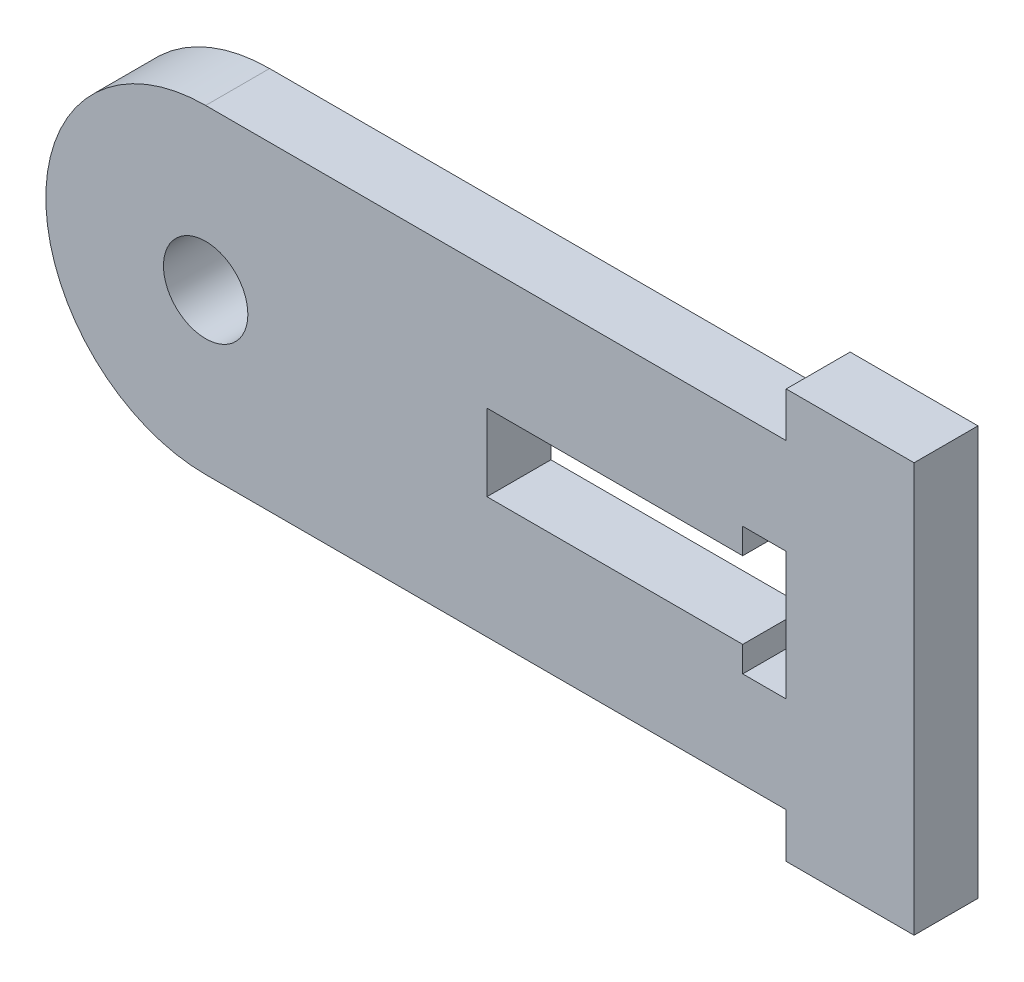
SolidWorks part; units mm, degrees
ref_plane "Front Plane" through (0, 0, 0) normal (0, 0, 1) x (1, 0, 0)
ref_plane "Top Plane" through (0, 0, 0) normal (0, 1, 0) x (1, 0, 0)
ref_plane "Right Plane" through (0, 0, 0) normal (1, 0, 0) x (0, 0, -1)
sketch "Sketch1" plane through (0, 0, 0) normal (0, 0, 1) x (1, 0, 0)
  line L0 (0, -6.25) -> (22.7, -6.25)
  line L1 (-12.7, 12.7) -> (12.7, 12.7)
  line L2 (-12.7, 12.7) -> (-12.7, -12.7)
  line L3 (-12.7, -12.7) -> (12.7, -12.7)
  line L4 (12.7, 12.7) -> (12.7, -12.7)
  line L5 (0, 6.25) -> (22.7, 6.25)
  line L6 (22.7, 6.25) -> (22.7, -6.25)
  circle A0 centre (0, 0) radius 1.65
  arc A1 (0, 6.25) -> (0, -6.25) centre (0, 0) ccw
  dimension "D1" = 3.3
  dimension "D3" = 25.4
  dimension "D4" = 25.4
  dimension "D5" = 12.7
  dimension "D6" = 12.7
  dimension "D7" = 10
extrude "Boss-Extrude1" add sketch "Sketch1" along normal blind 2.5 contours L5 A1 L0 L4 A0 | L6 L5 L4 L0
sketch "Sketch2" plane through (0, 0, 2.5) normal (0, 0, 1) x (1, 0, 0)
  line L1 (22.7, -8) -> (27.7, -8)
  line L2 (22.7, -8) -> (22.7, 8)
  line L3 (22.7, 8) -> (27.7, 8)
  line L4 (27.7, -8) -> (27.7, 8)
  circle A0 centre (0, 0) radius 1.65 construction
  dimension "D1" = 5
  dimension "D2" = 16
  dimension "D3" = 8
extrude "Boss-Extrude2" add sketch "Sketch2" against normal blind 2.5
sketch "Sketch3" plane through (0, 0, 2.5) normal (0, 0, 1) x (1, 0, 0)
  line L0 (22.7, 8) -> (22.7, 6.25) construction
  line L1 (22.7, 2.5) -> (21, 2.5)
  line L2 (22.7, 2.5) -> (22.7, -2.5)
  line L3 (22.7, -2.5) -> (21, -2.5)
  line L4 (21, 2.5) -> (21, -2.5)
  circle A0 centre (0, 0) radius 1.65 construction
  dimension "D1" = 1.7
  dimension "D2" = 0
  dimension "D3" = 5
  dimension "D4" = 2.5
extrude "Cut-Extrude1" cut sketch "Sketch3" against normal through all
sketch "Sketch5" plane through (0, 0, 2.5) normal (0, 0, 1) x (1, 0, 0)
  line L0 (21, 2.5) -> (21, -2.5) construction
  line L1 (21, -1.5) -> (11, -1.5)
  line L2 (21, -1.5) -> (21, 1.5)
  line L3 (21, 1.5) -> (11, 1.5)
  line L4 (11, -1.5) -> (11, 1.5)
  line L5 (22.7, 2.5) -> (21, 2.5) construction
  dimension "D1" = 3
  dimension "D2" = 1
  dimension "D3" = 10
extrude "Cut-Extrude2" cut sketch "Sketch5" against normal through all
sketch "Sketch6" plane through (27.7, 0, 0) normal (1, 0, 0) x (0, 0, -1)
  circle A0 centre (-1.1282, 0) radius 2.2529
